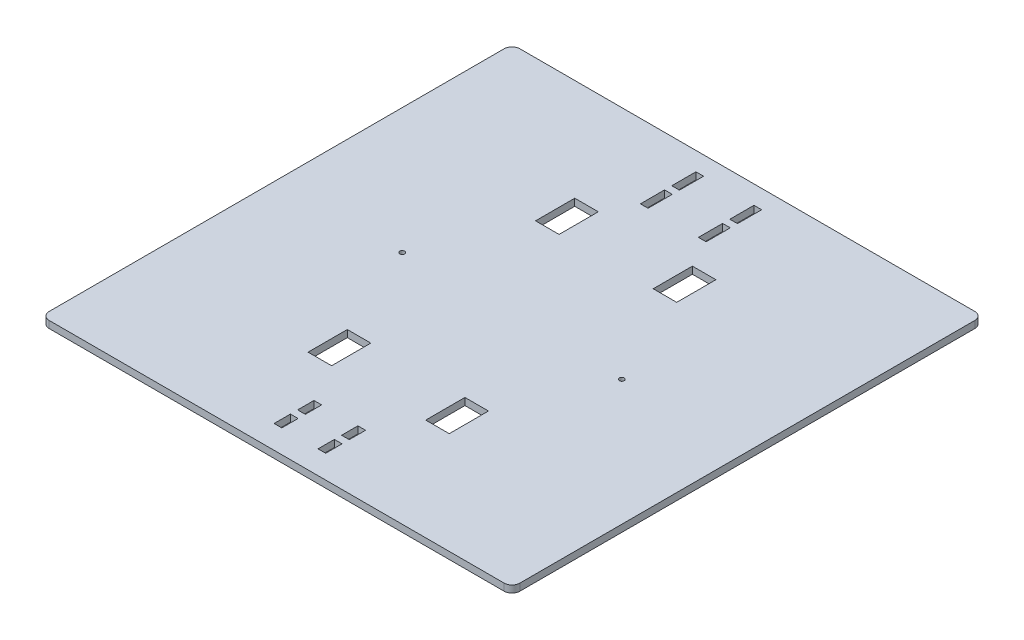
SolidWorks part; units mm, degrees
ref_plane "Front Plane" through (0, 0, 0) normal (0, 0, 1) x (1, 0, 0)
ref_plane "Top Plane" through (0, 0, 0) normal (0, 1, 0) x (1, 0, 0)
ref_plane "Right Plane" through (0, 0, 0) normal (1, 0, 0) x (0, 0, -1)
sketch "Sketch1" plane through (0, 0, 0) normal (0, 1, 0) x (1, 0, 0)
  line L1 (-150, -150) -> (150, -150)
  line L2 (-150, -150) -> (-150, 150)
  line L3 (-150, 150) -> (150, 150)
  line L4 (150, -150) -> (150, 150)
  line L5 (-150, -150) -> (150, 150) construction
  line L6 (-150, 150) -> (150, -150) construction
  point P0 (0, 0)
  dimension "D1" = 300
  dimension "D2" = 300
extrude "Boss-Extrude1" add sketch "Sketch1" along normal blind 4.5
sketch "Sketch2" plane through (0, 4.5, 0) normal (0, 1, 0) x (1, 0, 0)
  line L0 (0, 150) -> (0, -150) construction
  line L1 (150, 150) -> (-150, 150) construction
  line L2 (-150, -150) -> (150, -150) construction
sketch "Sketch3" plane through (0, 0, 0) normal (0, -1, 0) x (1, 0, 0)
  line L0 (20.75, -123) -> (16.25, -123) construction
  line L1 (20.75, -138) -> (16.25, -138) construction
  line L3 (20.75, -118) -> (16.25, -118) construction
  line L6 (20.75, -103) -> (16.25, -103) construction
  line L10 (-16.25, -103) -> (-20.75, -103) construction
  line L15 (-16.25, -118) -> (-20.75, -118) construction
  line L21 (-16.25, -138) -> (-20.75, -138) construction
  line L28 (-16.25, -123) -> (-20.75, -123) construction
  line L144 (20.75, -123) -> (16.25, -123) construction
  line L145 (20.75, -103) -> (16.25, -103) construction
  line L146 (-16.25, -103) -> (-20.75, -103) construction
  line L147 (-16.25, -123) -> (-20.75, -123) construction
  line L148 (-16.25, -118) -> (-20.75, -118) construction
  line L149 (20.75, -118) -> (16.25, -118) construction
  line L150 (20.75, -138) -> (16.25, -138) construction
  line L151 (-16.25, -138) -> (-20.75, -138) construction
  line L152 (20.75, -138) -> (20.75, -123) construction
  line L153 (16.25, -123) -> (16.25, -138) construction
  line L154 (20.75, -118) -> (20.75, -103) construction
  line L155 (16.25, -103) -> (16.25, -118) construction
  line L156 (-16.25, -118) -> (-16.25, -103) construction
  line L157 (-20.75, -103) -> (-20.75, -118) construction
  line L158 (-20.75, -123) -> (-20.75, -138) construction
  line L159 (-16.25, -138) -> (-16.25, -123) construction
  line L160 (20.95, -122.8) -> (16.05, -122.8)
  line L161 (16.05, -122.8) -> (16.05, -138.2)
  line L162 (20.95, -138.2) -> (16.05, -138.2)
  line L163 (20.95, -138.2) -> (20.95, -122.8)
  line L164 (20.95, -102.8) -> (16.05, -102.8)
  line L165 (16.05, -102.8) -> (16.05, -118.2)
  line L166 (20.95, -118.2) -> (16.05, -118.2)
  line L167 (20.95, -118.2) -> (20.95, -102.8)
  line L168 (-16.05, -102.8) -> (-20.95, -102.8)
  line L169 (-20.95, -102.8) -> (-20.95, -118.2)
  line L170 (-16.05, -118.2) -> (-20.95, -118.2)
  line L171 (-16.05, -118.2) -> (-16.05, -102.8)
  line L172 (-16.05, -122.8) -> (-20.95, -122.8)
  line L173 (-20.95, -122.8) -> (-20.95, -138.2)
  line L174 (-16.05, -138.2) -> (-20.95, -138.2)
  line L175 (-16.05, -138.2) -> (-16.05, -122.8)
  dimension "D1" = 0.2
extrude "Cut-Extrude1" cut sketch "Sketch3" against normal through all
ref_plane "Plane1" through (0, 0, 0) normal (-1, 0, 0) x (0, 0, 1)
sketch "Sketch4" plane through (0, 4.5, 0) normal (0, 1, 0) x (1, 0, 0)
  line L0 (-150, 0) -> (150, 0) construction
  line L1 (-150, 150) -> (-150, -150) construction
  line L2 (150, -150) -> (150, 150) construction
ref_plane "Plane2" through (0, 0, 0) normal (0, 0, 1) x (1, 0, 0)
sketch "Sketch6" plane through (0, 0, 0) normal (0, -1, 0) x (1, 0, 0)
  line L0 (45, -85) -> (30, -85) construction
  line L1 (30, -85) -> (30, -60) construction
  line L2 (30, -60) -> (45, -60) construction
  line L3 (45, -60) -> (45, -85) construction
  line L4 (45, 85) -> (45, 60) construction
  line L5 (30, 85) -> (45, 85) construction
  line L6 (30, 60) -> (30, 85) construction
  line L7 (45, 60) -> (30, 60) construction
  line L8 (-30, 60) -> (-45, 60) construction
  line L9 (-45, 60) -> (-45, 85) construction
  line L10 (-45, 85) -> (-30, 85) construction
  line L11 (-30, 85) -> (-30, 60) construction
  line L12 (-45, -60) -> (-30, -60) construction
  line L13 (-45, -85) -> (-45, -60) construction
  line L14 (-30, -85) -> (-45, -85) construction
  line L15 (-30, -60) -> (-30, -85) construction
  line L16 (45, -85) -> (30, -85)
  line L17 (30, -85) -> (30, -60)
  line L18 (30, -60) -> (45, -60)
  line L19 (45, -60) -> (45, -85)
  line L20 (45, 85) -> (45, 60)
  line L21 (30, 85) -> (45, 85)
  line L22 (30, 60) -> (30, 85)
  line L23 (45, 60) -> (30, 60)
  line L24 (-30, 60) -> (-45, 60)
  line L25 (-45, 60) -> (-45, 85)
  line L26 (-45, 85) -> (-30, 85)
  line L27 (-30, 85) -> (-30, 60)
  line L28 (-45, -60) -> (-30, -60)
  line L29 (-45, -85) -> (-45, -60)
  line L30 (-30, -85) -> (-45, -85)
  line L31 (-30, -60) -> (-30, -85)
extrude "Cut-Extrude2" cut sketch "Sketch6" against normal through all
sketch "Sketch7" plane through (0, 0, 0) normal (0, -1, 0) x (1, 0, 0)
  line L0 (11.75, 135) -> (16.25, 135) construction
  line L1 (-11.75, 135) -> (-16.25, 135) construction
  line L2 (-11.75, 120) -> (-16.25, 120) construction
  line L3 (11.75, 120) -> (16.25, 120) construction
  line L4 (11.75, 110) -> (16.25, 110) construction
  line L5 (-11.75, 110) -> (-16.25, 110) construction
  line L6 (-11.75, 125) -> (-16.25, 125) construction
  line L7 (11.75, 125) -> (16.25, 125) construction
  line L8 (11.75, 135) -> (16.25, 135) construction
  line L9 (-11.75, 135) -> (-16.25, 135) construction
  line L10 (-11.75, 120) -> (-16.25, 120) construction
  line L11 (11.75, 120) -> (16.25, 120) construction
  line L12 (11.75, 110) -> (16.25, 110) construction
  line L13 (-11.75, 110) -> (-16.25, 110) construction
  line L14 (-11.75, 125) -> (-16.25, 125) construction
  line L15 (11.75, 125) -> (16.25, 125) construction
  line L16 (16.25, 110) -> (16.25, 120) construction
  line L17 (11.75, 110) -> (11.75, 120) construction
  line L18 (11.75, 125) -> (11.75, 135) construction
  line L19 (16.25, 135) -> (16.25, 125) construction
  line L20 (-11.75, 125) -> (-11.75, 135) construction
  line L21 (-16.25, 135) -> (-16.25, 125) construction
  line L22 (-16.25, 120) -> (-16.25, 110) construction
  line L23 (-11.75, 110) -> (-11.75, 120) construction
  line L24 (11.55, 135.2) -> (16.45, 135.2)
  line L25 (16.45, 135.2) -> (16.45, 124.8)
  line L26 (11.55, 124.8) -> (16.45, 124.8)
  line L27 (11.55, 124.8) -> (11.55, 135.2)
  line L28 (-11.55, 135.2) -> (-16.45, 135.2)
  line L29 (-16.45, 135.2) -> (-16.45, 124.8)
  line L30 (-11.55, 124.8) -> (-16.45, 124.8)
  line L31 (-11.55, 124.8) -> (-11.55, 135.2)
  line L32 (-11.55, 120.2) -> (-16.45, 120.2)
  line L33 (-16.45, 120.2) -> (-16.45, 109.8)
  line L34 (-11.55, 109.8) -> (-16.45, 109.8)
  line L35 (-11.55, 109.8) -> (-11.55, 120.2)
  line L36 (11.55, 120.2) -> (16.45, 120.2)
  line L37 (16.45, 109.8) -> (16.45, 120.2)
  line L38 (11.55, 109.8) -> (16.45, 109.8)
  line L39 (11.55, 109.8) -> (11.55, 120.2)
  dimension "D1" = 0.2
extrude "Cut-Extrude3" cut sketch "Sketch7" against normal through all
sketch "Sketch8" plane through (0, 0, 0) normal (0, -1, 0) x (1, 0, 0)
  line L0 (-150, 0) -> (150, 0) construction
  line L1 (0, -150) -> (0, 150) construction
  line L2 (0, 0) -> (0, -145) construction
  circle A0 centre (70, 0) radius 1.55
  circle A1 centre (-70, 0) radius 1.55
  dimension "D1" = 70
extrude "Cut-Extrude4" cut sketch "Sketch8" against normal through all
fillet "Fillet1" radius 5 4 edges at (-150, 2.25, -150) (150, 2.25, -150) (150, 2.25, 150) (-150, 2.25, 150)
